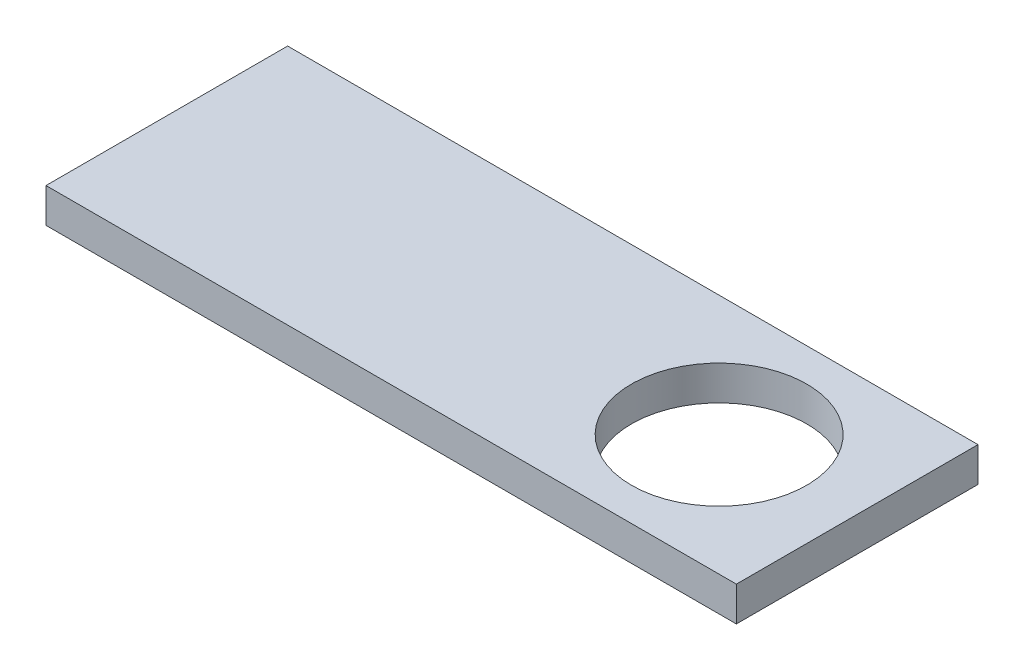
SolidWorks part; units mm, degrees
ref_plane "Front Plane" through (0, 0, 0) normal (0, 0, 1) x (1, 0, 0)
ref_plane "Top Plane" through (0, 0, 0) normal (0, 1, 0) x (1, 0, 0)
ref_plane "Right Plane" through (0, 0, 0) normal (1, 0, 0) x (0, 0, -1)
sketch "Sketch2" plane through (0, 0, 0) normal (0, 1, 0) x (1, 0, 0)
  line L1 (-100, -35) -> (100, -35)
  line L2 (-100, -35) -> (-100, 35)
  line L3 (-100, 35) -> (100, 35)
  line L4 (100, -35) -> (100, 35)
  line L5 (-100, -35) -> (100, 35) construction
  line L6 (-100, 35) -> (100, -35) construction
  circle A0 centre (60, 0) radius 25.4
  point P0 (0, 0)
  dimension "D3" = 50.8
  dimension "D1" = 200
  dimension "D2" = 70
  dimension "D4" = 40
extrude "Boss-Extrude1" add sketch "Sketch2" along normal mid plane 10
